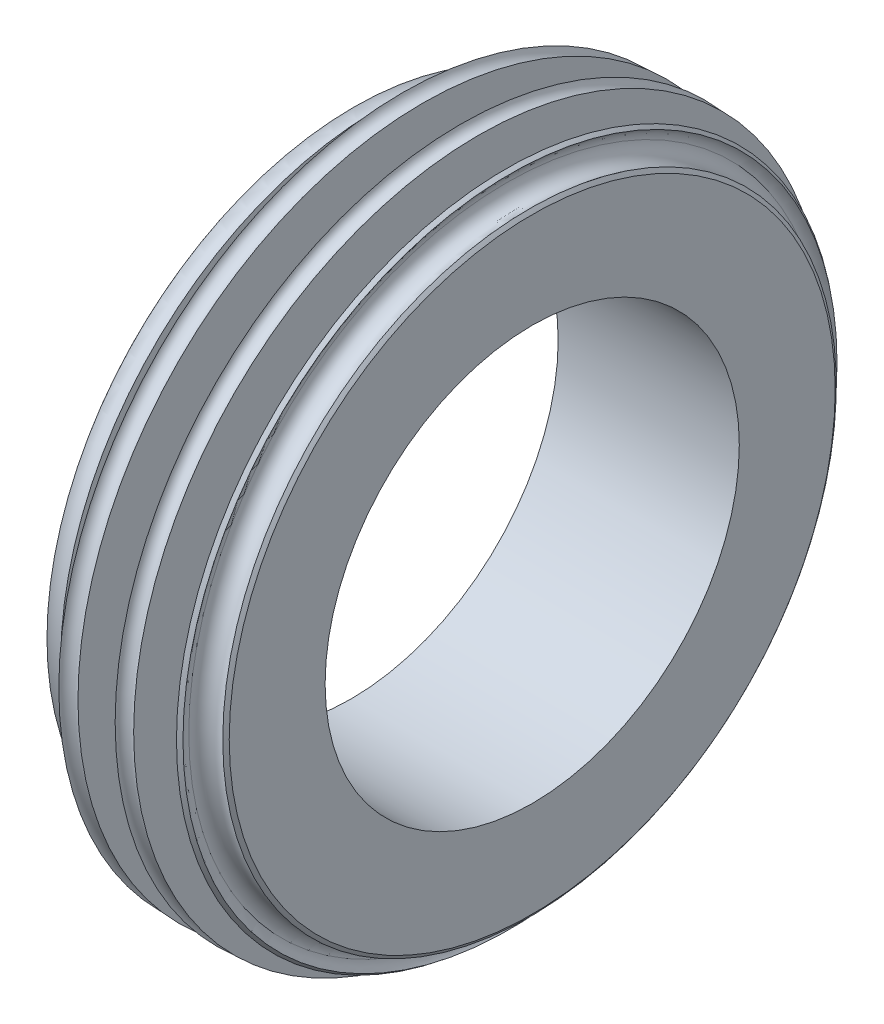
SolidWorks part; units mm, degrees
ref_plane "Front Plane" through (0, 0, 0) normal (0, 0, 1) x (1, 0, 0)
ref_plane "Top Plane" through (0, 0, 0) normal (0, 1, 0) x (1, 0, 0)
ref_plane "Right Plane" through (0, 0, 0) normal (1, 0, 0) x (0, 0, -1)
sketch "Sketch1" plane through (0, 0, 0) normal (0, 0, 1) x (1, 0, 0)
  line L0 (-37.2774, 0) -> (38.4363, 0) construction
  line L5 (-13.134, 30.0344) -> (13.134, 30.0344)
  line L6 (-13.134, 30.0344) -> (-13.134, 43.941)
  line L8 (13.134, 30.0344) -> (13.134, 43.941)
  line L9 (-13.134, 30.0344) -> (13.134, 43.941) construction
  line L10 (-13.134, 43.941) -> (13.134, 30.0344) construction
  arc A0 (-13.134, 43.941) -> (13.134, 43.941) centre (0, 35.0374) cw
  point P0 (0, 36.9877)
revolve "Revolve1" add sketch "Sketch1" angle 360 about L0
sketch "Sketch2" plane through (0, 0, 0) normal (0, 0, 1) x (1, 0, 0)
  line L0 (30.0261, 0) -> (-32.7714, 0) construction
  line L1 (-2.7452, 41.3285) -> (2.7452, 41.3285)
  line L2 (-2.7452, 41.3285) -> (-2.7452, 60.4812)
  line L3 (-2.7452, 60.4812) -> (2.7452, 60.4812)
  line L4 (2.7452, 41.3285) -> (2.7452, 60.4812)
  line L5 (-2.7452, 41.3285) -> (2.7452, 60.4812) construction
  line L6 (-2.7452, 60.4812) -> (2.7452, 41.3285) construction
  line L7 (-9.0347, 56.873) -> (-5.6621, 56.873)
  line L8 (-9.0347, 56.873) -> (-9.0347, 41.3285)
  line L9 (-9.0347, 41.3285) -> (-5.6621, 41.3285)
  line L10 (-5.6621, 56.873) -> (-5.6621, 41.3285)
  line L11 (-9.0347, 56.873) -> (-5.6621, 41.3285) construction
  line L12 (-9.0347, 41.3285) -> (-5.6621, 56.873) construction
  line L13 (9.3779, 56.873) -> (5.3189, 56.873)
  line L14 (9.3779, 56.873) -> (9.3779, 41.3285)
  line L15 (9.3779, 41.3285) -> (5.3189, 41.3285)
  line L16 (5.3189, 56.873) -> (5.3189, 41.3285)
  line L17 (9.3779, 56.873) -> (5.3189, 41.3285) construction
  line L18 (9.3779, 41.3285) -> (5.3189, 56.873) construction
  arc A0 (13.134, 43.941) -> (-13.134, 43.941) centre (0, 35.0374) ccw construction
  point P0 (0, 50.9049)
  point P8 (-7.3484, 49.1007)
  point P13 (7.3484, 49.1007)
revolve "Cut-Revolve1" cut sketch "Sketch2" angle 360 about L0
sketch "Sketch4" plane through (0, 0, 0) normal (0, 0, 1) x (1, 0, 0)
  line L0 (-21.1878, 0) -> (20.8512, 0) construction
  circle A0 centre (-4.2229, 50.3326) radius 1.5147
  arc A1 (-2.7452, 50.6656) -> (-5.6621, 49.8603) centre (0, 35.0374) ccw construction
  circle A2 centre (4.0463, 50.3803) radius 1.332
  arc A3 (5.3189, 49.9868) -> (2.7452, 50.6656) centre (0, 35.0374) ccw construction
  circle A4 centre (11.4233, 46.0503) radius 2.0454
  arc A5 (13.134, 43.941) -> (9.3779, 47.8371) centre (0, 35.0374) ccw construction
  circle A8 centre (-11.2761, 46.201) radius 2.2413
  arc A9 (-9.0347, 48.0815) -> (-13.134, 43.941) centre (0, 35.0374) ccw construction
revolve "Cut-Revolve2" cut sketch "Sketch4" angle 360 about L0
